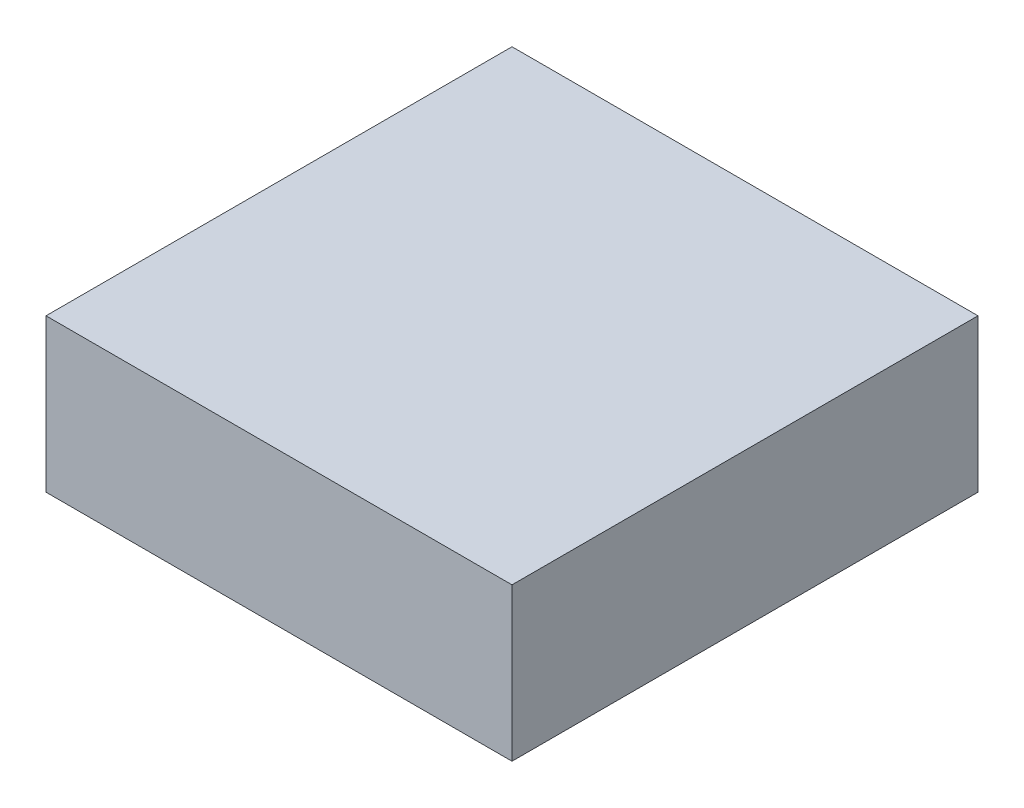
SolidWorks part; units mm, degrees
ref_plane "Front Plane" through (0, 0, 0) normal (0, 0, 1) x (1, 0, 0)
ref_plane "Top Plane" through (0, 0, 0) normal (0, 1, 0) x (1, 0, 0)
ref_plane "Right Plane" through (0, 0, 0) normal (1, 0, 0) x (0, 0, -1)
sketch "Sketch1" plane through (0, 0, 0) normal (0, 1, 0) x (1, 0, 0)
  line L1 (3.05, -3.05) -> (-3.05, -3.05)
  line L2 (3.05, -3.05) -> (3.05, 3.05)
  line L3 (3.05, 3.05) -> (-3.05, 3.05)
  line L4 (-3.05, -3.05) -> (-3.05, 3.05)
  line L5 (3.05, -3.05) -> (-3.05, 3.05) construction
  line L6 (3.05, 3.05) -> (-3.05, -3.05) construction
  point P0 (0, 0)
  dimension "D1" = 6.1
  dimension "D2" = 6.1
extrude "Boss-Extrude1" add sketch "Sketch1" along normal blind 2
